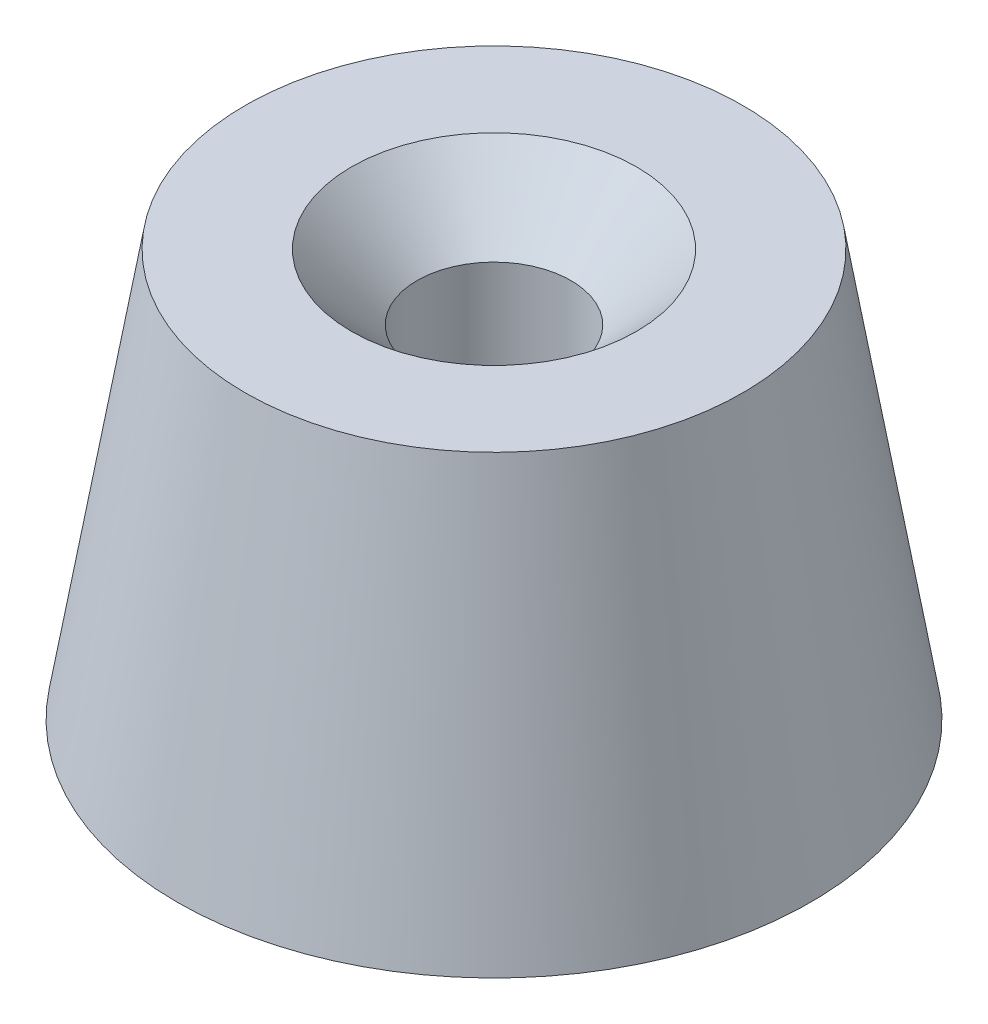
SolidWorks part; units mm, degrees
material "Rubber"
ref_plane "Front Plane" through (0, 0, 0) normal (0, 0, 1) x (1, 0, 0)
ref_plane "Top Plane" through (0, 0, 0) normal (0, 1, 0) x (1, 0, 0)
ref_plane "Right Plane" through (0, 0, 0) normal (1, 0, 0) x (0, 0, -1)
sketch "Sketch1" plane through (0, 0, 0) normal (0, 1, 0) x (1, 0, 0)
  circle A0 centre (0, 0) radius 7
  dimension "D1" = 14
ref_plane "Plane1" through (0, 9, 0) normal (0, 1, 0) x (1, 0, 0)
sketch "Sketch2" plane through (0, 9, 0) normal (0, 1, 0) x (1, 0, 0)
  circle A0 centre (0, 0) radius 5.5
  dimension "D1" = 11
loft "Loft1" add profiles "Sketch2", "Sketch1"
hole_wizard "CSK for M3 Flat Head Machine Screw1" positions "Sketch3" profile "Sketch4" countersink size "M3" standard "ANSI Metric" end condition through all
sketch "Sketch3" plane through (0, 9, 0) normal (0, 1, 0) x (1, 0, 0)
  point P0 (0, 0)
sketch "Sketch4" plane through (0, 9, 0) normal (1, 0, 0) x (0, 0, 1)
  line L0 (0, 0) -> (0, 9.0001)
  line L1 (0, 9.0001) -> (1.7, 9.0001)
  line L2 (1.7, 9.0001) -> (1.7, 1.45)
  line L3 (1.7, 1.45) -> (3.15, 0)
  line L5 (3.15, 0) -> (0, 0)
  line L6 (-1.7, 1.45) -> (-3.15, 0) construction
  line L11 (0, -6.35) -> (0, 107.95) construction
  dimension "Thru Hole Dia." = 3.4
  dimension "Thru Hole Depth" = 9.0001
  dimension "Near C'Sink Dia." = 6.3
  dimension "Near C'Sink Angle" = 90
